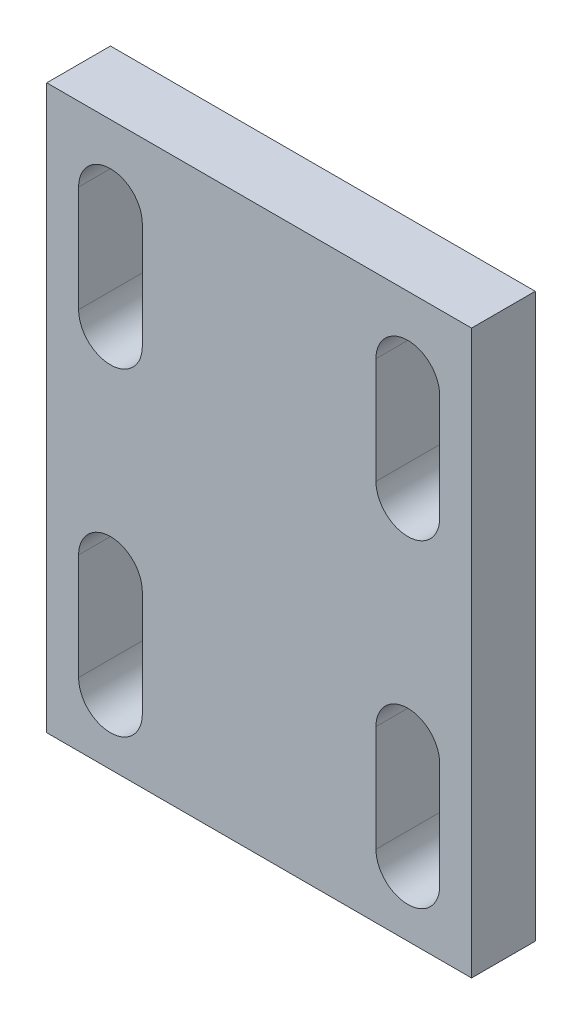
SolidWorks part; units mm, degrees
ref_plane "Спереди" through (0, 0, 0) normal (0, 0, 1) x (1, 0, 0)
ref_plane "Сверху" through (0, 0, 0) normal (0, 1, 0) x (1, 0, 0)
ref_plane "Справа" through (0, 0, 0) normal (1, 0, 0) x (0, 0, -1)
sketch "Sketch1" plane through (0, 0, 0) normal (0, 0, 1) x (1, 0, 0)
  line L0 (4.5, 8) -> (4.5, 3)
  line L1 (0, 0) -> (20, 0)
  line L2 (0, 0) -> (0, 26.5)
  line L3 (0, 26.5) -> (20, 26.5)
  line L4 (20, 0) -> (20, 26.5)
  line L5 (1.5, 8) -> (1.5, 3)
  line L6 (18.5, 8) -> (18.5, 3)
  line L7 (15.5, 8) -> (15.5, 3)
  line L8 (18.5, 23) -> (18.5, 18)
  line L9 (15.5, 23) -> (15.5, 18)
  line L10 (4.5, 23) -> (4.5, 18)
  line L11 (1.5, 23) -> (1.5, 18)
  arc A0 (1.5, 3) -> (4.5, 3) centre (3, 3) ccw
  arc A1 (4.5, 8) -> (1.5, 8) centre (3, 8) ccw
  arc A2 (15.5, 3) -> (18.5, 3) centre (17, 3) ccw
  arc A3 (18.5, 8) -> (15.5, 8) centre (17, 8) ccw
  arc A4 (15.5, 18) -> (18.5, 18) centre (17, 18) ccw
  arc A5 (18.5, 23) -> (15.5, 23) centre (17, 23) ccw
  arc A6 (1.5, 18) -> (4.5, 18) centre (3, 18) ccw
  arc A7 (4.5, 23) -> (1.5, 23) centre (3, 23) ccw
  dimension "D3" = 3
  dimension "D6" = 3
  dimension "D1" = 26.5
  dimension "D2" = 20
  dimension "D4" = 3
  dimension "D5" = 3
  dimension "D7" = 5
  dimension "D8" = 2
  dimension "D9" = 2
extrude "Boss-Extrude1" add sketch "Sketch1" along normal blind 3
